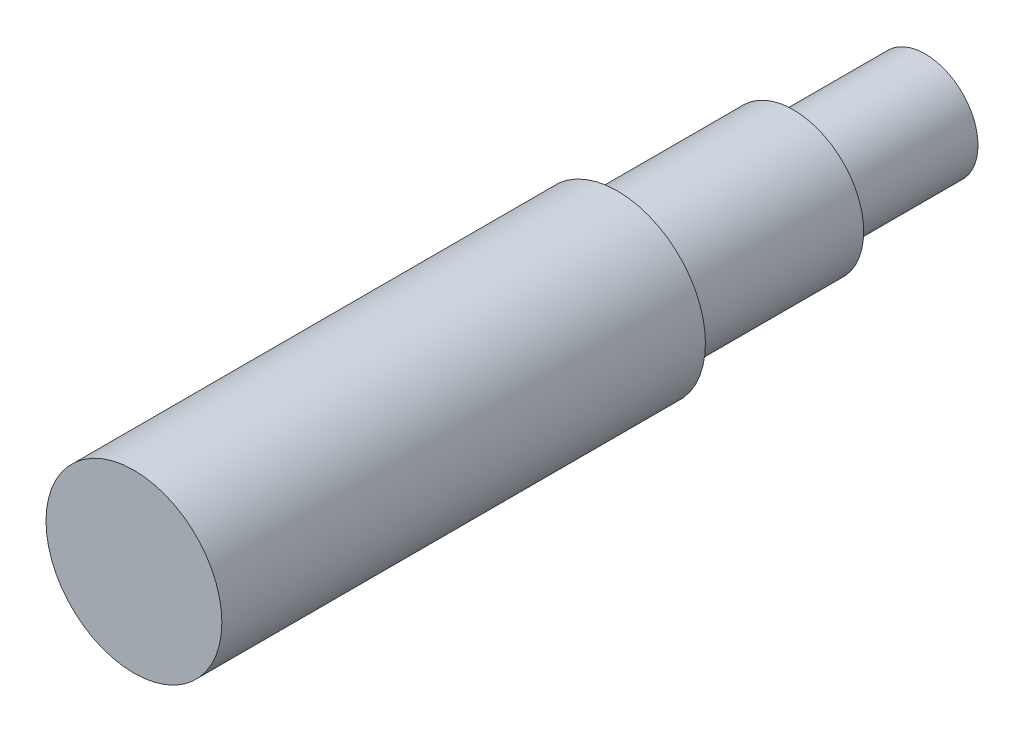
SolidWorks part; units mm, degrees
ref_plane "前视基准面" through (0, 0, 0) normal (0, 0, 1) x (1, 0, 0)
ref_plane "上视基准面" through (0, 0, 0) normal (0, 1, 0) x (1, 0, 0)
ref_plane "右视基准面" through (0, 0, 0) normal (1, 0, 0) x (0, 0, -1)
other "Configuration Table"
sketch "草图1" plane through (0, 0, 0) normal (1, 0, 0) x (0, 0, -1)
  line L0 (0, 0) -> (0, 20)
  line L1 (0, 20) -> (110, 20)
  line L2 (110, 20) -> (110, 16)
  line L3 (110, 16) -> (150, 16)
  line L4 (150, 16) -> (150, 12)
  line L5 (150, 12) -> (180, 12)
  line L6 (180, 12) -> (180, 0)
  line L7 (180, 0) -> (0, 0)
  line L8 (0, 0) -> (180, 0) construction
revolve "旋转1" add sketch "草图1" angle 360 about L8
